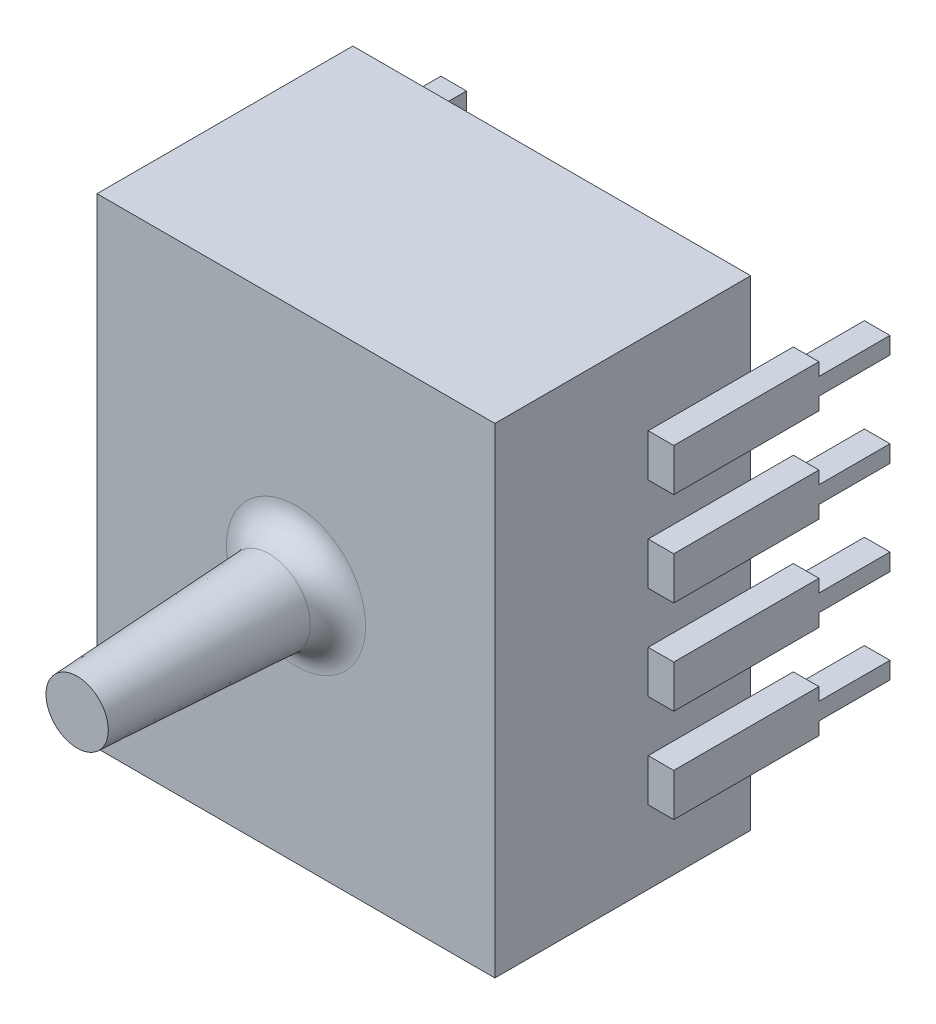
SolidWorks part; units mm, degrees
ref_plane "Face" through (0, 0, 0) normal (0, 0, 1) x (1, 0, 0)
ref_plane "Dessus" through (0, 0, 0) normal (0, 1, 0) x (1, 0, 0)
ref_plane "Droite" through (0, 0, 0) normal (1, 0, 0) x (0, 0, -1)
sketch "Esquisse1" plane through (0, 0, 0) normal (0, 0, 1) x (1, 0, 0)
  line L1 (0, 0) -> (14, 0)
  line L2 (0, 0) -> (0, 16.9)
  line L3 (0, 16.9) -> (14, 16.9)
  line L4 (14, 0) -> (14, 16.9)
  dimension "D1" = 16.9
  dimension "D2" = 14
extrude "Base-Extrusion" add sketch "Esquisse1" along normal blind 9
sketch "Esquisse4" plane through (0, 0, 0) normal (-1, 0, 0) x (0, 0, 1)
  line L0 (3.6075, 13.9806) -> (-1.5, 13.9806)
  line L1 (3.6075, 13.9806) -> (3.6075, 12.4806)
  line L2 (-1.5, 13.9806) -> (-1.5, 13.5306)
  line L3 (3.6075, 12.4806) -> (-1.5, 12.4806)
  line L4 (9, 16.9) -> (9, 0) construction
  line L5 (3.6075, 13.2306) -> (-4.5586, 13.2306) construction
  line L6 (-1.5, 13.5306) -> (-4, 13.5306)
  line L7 (3.6075, 10.6806) -> (-1.5, 10.6806)
  line L8 (-4, 13.5306) -> (-4, 12.9306)
  line L9 (-1.5, 12.9306) -> (-4, 12.9306)
  line L10 (-1.5, 12.9306) -> (-1.5, 12.4806)
  line L11 (3.6075, 10.6806) -> (3.6075, 9.1806)
  line L12 (-1.5, 10.6806) -> (-1.5, 10.2306)
  line L13 (3.6075, 9.1806) -> (-1.5, 9.1806)
  line L14 (-1.5, 10.2306) -> (-4, 10.2306)
  line L15 (-4, 10.2306) -> (-4, 9.6306)
  line L16 (-1.5, 9.6306) -> (-4, 9.6306)
  line L17 (-1.5, 9.6306) -> (-1.5, 9.1806)
  line L18 (3.6075, 7.3806) -> (-1.5, 7.3806)
  line L19 (3.6075, 7.3806) -> (3.6075, 5.8806)
  line L20 (-1.5, 7.3806) -> (-1.5, 6.9306)
  line L21 (3.6075, 5.8806) -> (-1.5, 5.8806)
  line L22 (-1.5, 6.9306) -> (-4, 6.9306)
  line L23 (-4, 6.9306) -> (-4, 6.3306)
  line L24 (-1.5, 6.3306) -> (-4, 6.3306)
  line L25 (-1.5, 6.3306) -> (-1.5, 5.8806)
  line L26 (3.6075, 4.0806) -> (-1.5, 4.0806)
  line L27 (3.6075, 4.0806) -> (3.6075, 2.5806)
  line L28 (-1.5, 4.0806) -> (-1.5, 3.6306)
  line L29 (3.6075, 2.5806) -> (-1.5, 2.5806)
  line L30 (-1.5, 3.6306) -> (-4, 3.6306)
  line L31 (-4, 3.6306) -> (-4, 3.0306)
  line L32 (-1.5, 3.0306) -> (-4, 3.0306)
  line L33 (-1.5, 3.0306) -> (-1.5, 2.5806)
  dimension "D1" = 1.5
  dimension "D2" = 10.5
  dimension "D3" = 0.6
  dimension "D4" = 2.5
extrude "Extrusion1" add sketch "Esquisse4" along normal blind 0.9
sketch "Esquisse5" plane through (14, 0, 0) normal (1, 0, 0) x (0, 0, -1)
  line L8 (1.5, 13.9806) -> (-3.6075, 13.9806)
  line L9 (1.5, 13.5306) -> (1.5, 13.9806)
  line L10 (4, 13.5306) -> (1.5, 13.5306)
  line L11 (4, 12.9306) -> (4, 13.5306)
  line L12 (1.5, 12.9306) -> (4, 12.9306)
  line L13 (1.5, 12.4806) -> (1.5, 12.9306)
  line L14 (-3.6075, 12.4806) -> (1.5, 12.4806)
  line L15 (-3.6075, 13.9806) -> (-3.6075, 12.4806)
  line L16 (1.5, 13.9806) -> (-3.6075, 13.9806)
  line L17 (1.5, 13.5306) -> (1.5, 13.9806)
  line L18 (4, 13.5306) -> (1.5, 13.5306)
  line L19 (4, 12.9306) -> (4, 13.5306)
  line L20 (1.5, 12.9306) -> (4, 12.9306)
  line L21 (1.5, 12.4806) -> (1.5, 12.9306)
  line L22 (-3.6075, 12.4806) -> (1.5, 12.4806)
  line L23 (-3.6075, 13.9806) -> (-3.6075, 12.4806)
  line L24 (1.5, 7.3806) -> (-3.6075, 7.3806)
  line L25 (1.5, 6.9306) -> (1.5, 7.3806)
  line L26 (4, 6.9306) -> (1.5, 6.9306)
  line L27 (4, 6.3306) -> (4, 6.9306)
  line L28 (1.5, 6.3306) -> (4, 6.3306)
  line L29 (1.5, 5.8806) -> (1.5, 6.3306)
  line L30 (-3.6075, 5.8806) -> (1.5, 5.8806)
  line L31 (-3.6075, 7.3806) -> (-3.6075, 5.8806)
  line L32 (1.5, 7.3806) -> (-3.6075, 7.3806)
  line L33 (1.5, 6.9306) -> (1.5, 7.3806)
  line L34 (4, 6.9306) -> (1.5, 6.9306)
  line L35 (4, 6.3306) -> (4, 6.9306)
  line L36 (1.5, 6.3306) -> (4, 6.3306)
  line L37 (1.5, 5.8806) -> (1.5, 6.3306)
  line L38 (-3.6075, 5.8806) -> (1.5, 5.8806)
  line L39 (-3.6075, 7.3806) -> (-3.6075, 5.8806)
  line L40 (-3.6075, 10.6806) -> (-3.6075, 9.1806)
  line L41 (1.5, 10.6806) -> (-3.6075, 10.6806)
  line L42 (1.5, 10.2306) -> (1.5, 10.6806)
  line L43 (4, 10.2306) -> (1.5, 10.2306)
  line L44 (4, 9.6306) -> (4, 10.2306)
  line L45 (1.5, 9.6306) -> (4, 9.6306)
  line L46 (1.5, 9.1806) -> (1.5, 9.6306)
  line L47 (-3.6075, 9.1806) -> (1.5, 9.1806)
  line L48 (-3.6075, 10.6806) -> (-3.6075, 9.1806)
  line L49 (1.5, 10.6806) -> (-3.6075, 10.6806)
  line L50 (1.5, 10.2306) -> (1.5, 10.6806)
  line L51 (4, 10.2306) -> (1.5, 10.2306)
  line L52 (4, 9.6306) -> (4, 10.2306)
  line L53 (1.5, 9.6306) -> (4, 9.6306)
  line L54 (1.5, 9.1806) -> (1.5, 9.6306)
  line L55 (-3.6075, 9.1806) -> (1.5, 9.1806)
  line L56 (-3.6075, 4.0806) -> (-3.6075, 2.5806)
  line L57 (1.5, 4.0806) -> (-3.6075, 4.0806)
  line L58 (1.5, 3.6306) -> (1.5, 4.0806)
  line L59 (4, 3.6306) -> (1.5, 3.6306)
  line L60 (4, 3.0306) -> (4, 3.6306)
  line L61 (1.5, 3.0306) -> (4, 3.0306)
  line L62 (1.5, 2.5806) -> (1.5, 3.0306)
  line L63 (-3.6075, 2.5806) -> (1.5, 2.5806)
  line L64 (-3.6075, 4.0806) -> (-3.6075, 2.5806)
  line L65 (1.5, 4.0806) -> (-3.6075, 4.0806)
  line L66 (1.5, 3.6306) -> (1.5, 4.0806)
  line L67 (4, 3.6306) -> (1.5, 3.6306)
  line L68 (4, 3.0306) -> (4, 3.6306)
  line L69 (1.5, 3.0306) -> (4, 3.0306)
  line L70 (1.5, 2.5806) -> (1.5, 3.0306)
  line L71 (-3.6075, 2.5806) -> (1.5, 2.5806)
  dimension "D1" = 0
  dimension "D2" = 0
  dimension "D3" = 0
  dimension "D4" = 0
extrude "Extrusion2" add sketch "Esquisse5" along normal blind 0.9
sketch "Esquisse6" plane through (0, 0, 9) normal (0, 0, 1) x (1, 0, 0)
  line L0 (7, 16.9) -> (7, -0.574) construction
  line L1 (14, 16.9) -> (0, 16.9) construction
  line L2 (0, 8.45) -> (13.5399, 8.45) construction
  line L3 (0, 16.9) -> (0, 0) construction
  circle A0 centre (7, 8.45) radius 1.5
extrude "Extrusion3" add sketch "Esquisse6" along normal blind 7.7 draft 3
fillet "Congé1" radius 1 1 edges at (5.5, 8.45, 9)
